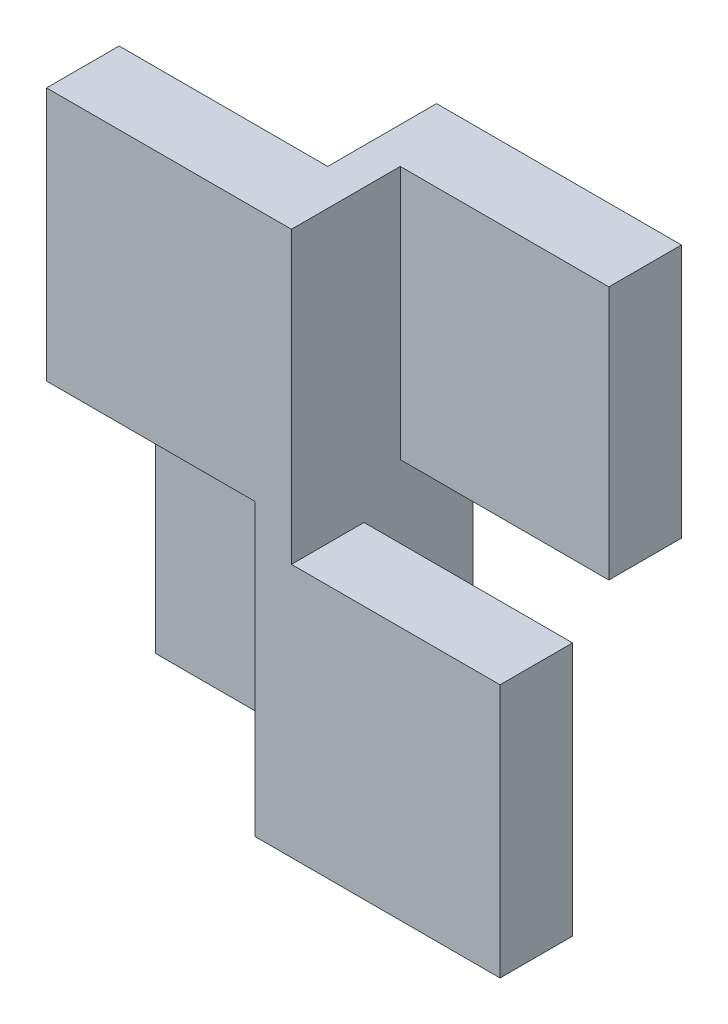
SolidWorks part; units mm, degrees
ref_plane "Front Plane" through (0, 0, 0) normal (0, 0, 1) x (1, 0, 0)
ref_plane "Top Plane" through (0, 0, 0) normal (0, 1, 0) x (1, 0, 0)
ref_plane "Right Plane" through (0, 0, 0) normal (1, 0, 0) x (0, 0, -1)
sketch "Sketch1" plane through (0, 0, 0) normal (0, 0, 1) x (1, 0, 0)
  line L1 (0, 0) -> (0.25, 0)
  line L2 (0, 0) -> (0, 0.3)
  line L3 (0, 0.3) -> (0.25, 0.3)
  line L4 (0.25, 0) -> (0.25, 0.3)
  dimension "D1" = 0.25
  dimension "D2" = 0.3
extrude "Boss-Extrude1" add sketch "Sketch1" along normal blind 0.1 contours L2 L3 L4 L1
sketch "Sketch2" plane through (0, 0, 0) normal (-1, 0, 0) x (0, 0, 1)
  line L0 (0, 0.15) -> (0.1, 0.15) construction
  line L1 (0, 0) -> (0, 0.3) construction
  line L2 (0.1, 0) -> (0.1, 0.3) construction
  line L3 (0.05, 0.3) -> (0.05, 0) construction
  line L4 (0.1, 0.3) -> (0, 0.3) construction
  line L5 (0.1, 0) -> (0, 0) construction
  line L6 (0, 0.16) -> (0.1, 0.16) construction
  line L7 (0.1, 0.14) -> (0, 0.14) construction
  line L8 (0.06, 0.3) -> (0.06, 0) construction
  line L9 (0.04, 0) -> (0.04, 0.3) construction
  line L10 (0, 0.3) -> (0.06, 0.3)
  line L11 (0.06, 0.3) -> (0.06, 0.16)
  line L12 (0.06, 0.16) -> (0.1, 0.16)
  line L13 (0.1, 0.16) -> (0.1, 0)
  line L14 (0.1, 0) -> (0.04, 0)
  line L15 (0.04, 0) -> (0.04, 0.14)
  line L16 (0.04, 0.14) -> (0, 0.14)
  line L17 (0, 0.14) -> (0, 0.3)
  dimension "D1" = 0.01
  dimension "D2" = 0.01
  dimension "D3" = 0.01
  dimension "D4" = 0.01
extrude "Cut-Extrude1" cut sketch "Sketch2" against normal blind 0.115
sketch "Sketch4" plane through (0.25, 0, 0) normal (1, 0, 0) x (0, 0, -1)
  line L0 (-0.05, 0.3) -> (-0.05, 0) construction
  line L1 (-0.1, 0.3) -> (0, 0.3) construction
  line L2 (-0.1, 0) -> (0, 0) construction
  line L3 (-0.1, 0.15) -> (0, 0.15) construction
  line L4 (-0.1, 0) -> (-0.1, 0.3) construction
  line L5 (0, 0) -> (0, 0.3) construction
  line L6 (0, 0.16) -> (-0.1, 0.16) construction
  line L7 (0, 0.14) -> (-0.1, 0.14) construction
  line L8 (-0.06, 0.3) -> (-0.06, 0) construction
  line L9 (-0.04, 0) -> (-0.04, 0.3) construction
  line L10 (-0.1, 0.14) -> (-0.1, 0.3)
  line L11 (-0.1, 0.3) -> (-0.04, 0.3)
  line L12 (-0.04, 0.3) -> (-0.04, 0.16)
  line L13 (-0.04, 0.16) -> (0, 0.16)
  line L14 (0, 0.16) -> (0, 0)
  line L15 (0, 0) -> (-0.06, 0)
  line L16 (-0.06, 0) -> (-0.06, 0.14)
  line L17 (-0.06, 0.14) -> (-0.1, 0.14)
  dimension "D1" = 0.01
  dimension "D2" = 0.01
  dimension "D3" = 0.01
  dimension "D4" = 0.01
extrude "Cut-Extrude2" cut sketch "Sketch4" against normal blind 0.115
equation "\"t\"= 0.25'thickness of the sheets"
equation "\"t_cf\"= 0.115'thickness of single carbon fiber layer"
equation "\"t_kapton\"= 0.025'thickness of single Kapton flex layer"
equation "\"t_fr4\"= 0.1'thickness of FR4 with copper layer"
equation "\"joint_flex\"= 0.1'Width of flextures gap"
equation "\"joint_flex_eff\"= 0.02'Width of flecture after castelation"
equation "\"joint_fold\"= 0.2'Width of folding joints for 90deg fold"
equation "\"gap_tolerance\"= 0.002'Width to have interfecence fit between carbon fiber inserts"
equation "\"assemble_angle\"= 90'Angle of assembly parts"
equation "\"link_lift\"= 0.5'Actuation linkage amplification for the lift motion"
equation "\"link_swing\"= 0.45'Actuation linkage amplification for the swing motion"
equation "\"D1@Sketch1\"=\"t\""
equation "\"D1@Boss-Extrude1\"=\"joint_flex\""
equation "\"D3@Sketch2\"=\"joint_flex_eff\"/2"
equation "\"D4@Sketch2\"=\"joint_flex_eff\"/2"
equation "\"D1@Cut-Extrude1\"=\"t_cf\""
equation "\"D3@Sketch4\"=\"joint_flex_eff\"/2"
equation "\"D4@Sketch4\"=\"joint_flex_eff\"/2"
equation "\"D1@Cut-Extrude2\"=\"t_cf\""
